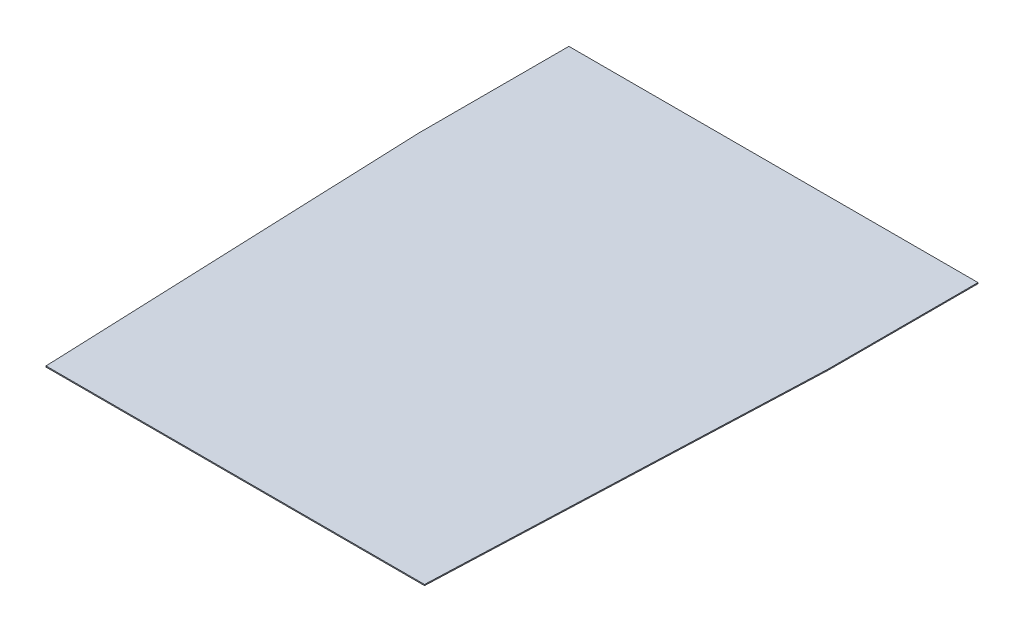
SolidWorks part; units mm, degrees
ref_plane "Front Plane" through (0, 0, 0) normal (0, 0, 1) x (1, 0, 0)
ref_plane "Top Plane" through (0, 0, 0) normal (0, 1, 0) x (1, 0, 0)
ref_plane "Right Plane" through (0, 0, 0) normal (1, 0, 0) x (0, 0, -1)
sketch "Sketch5" plane through (0, 0, 0) normal (0, 1, 0) x (1, 0, 0)
  line L0 (0, 0) -> (628, 0)
  line L3 (604.5128, -826.1) -> (509.77, -1078.5685)
  line L4 (509.77, -1078.5685) -> (118.23, -1078.5685)
  line L5 (118.23, -1078.5685) -> (23.4872, -826.1)
  line L6 (23.4872, -826.1) -> (0, -230.8)
  line L7 (0, -230.8) -> (0, 0)
  line L10 (628, 0) -> (628, -230.8)
  line L11 (628, -230.8) -> (604.5128, -826.1)
  dimension "D1" = 90
  dimension "D2" = 230.8
  dimension "D3" = 161.69
  dimension "D4" = 161.69
  dimension "D5" = 595.3
  dimension "D6" = 628
  dimension "D7" = 391.54
  dimension "D8" = 269.66
  dimension "D9" = 269.66
  dimension "D10" = 595.3
  dimension "D11" = 230.8
extrude "Boss-Extrude3" add sketch "Sketch5" along normal blind 1.6
sketch "Sketch6" plane through (0, 1.6, 0) normal (0, 1, 0) x (1, 0, 0)
  line L0 (23.4872, -826.1) -> (604.5128, -826.1)
  line L1 (604.5128, -826.1) -> (509.77, -1078.5685)
  line L2 (509.77, -1078.5685) -> (118.23, -1078.5685)
  line L3 (118.23, -1078.5685) -> (23.4872, -826.1)
extrude "Cut-Extrude3" cut sketch "Sketch6" against normal through all
